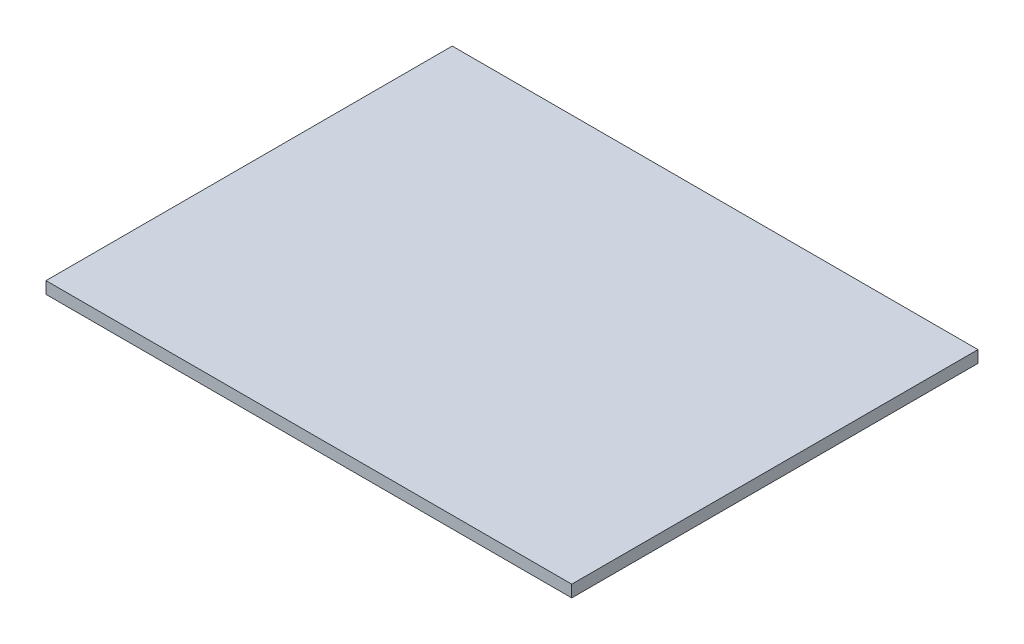
SolidWorks part; units mm, degrees
ref_plane "Front Plane" through (0, 0, 0) normal (0, 0, 1) x (1, 0, 0)
ref_plane "Top Plane" through (0, 0, 0) normal (0, 1, 0) x (1, 0, 0)
ref_plane "Right Plane" through (0, 0, 0) normal (1, 0, 0) x (0, 0, -1)
sketch "Sketch1" plane through (0, 0, 0) normal (0, 1, 0) x (1, 0, 0)
  line L1 (-139.7, -107.95) -> (139.7, -107.95)
  line L2 (-139.7, -107.95) -> (-139.7, 107.95)
  line L3 (-139.7, 107.95) -> (139.7, 107.95)
  line L4 (139.7, -107.95) -> (139.7, 107.95)
  line L5 (-139.7, -107.95) -> (139.7, 107.95) construction
  line L6 (-139.7, 107.95) -> (139.7, -107.95) construction
  point P0 (0, 0)
  dimension "D1" = 215.9
  dimension "D2" = 279.4
extrude "Boss-Extrude1" add sketch "Sketch1" along normal blind 6.35
